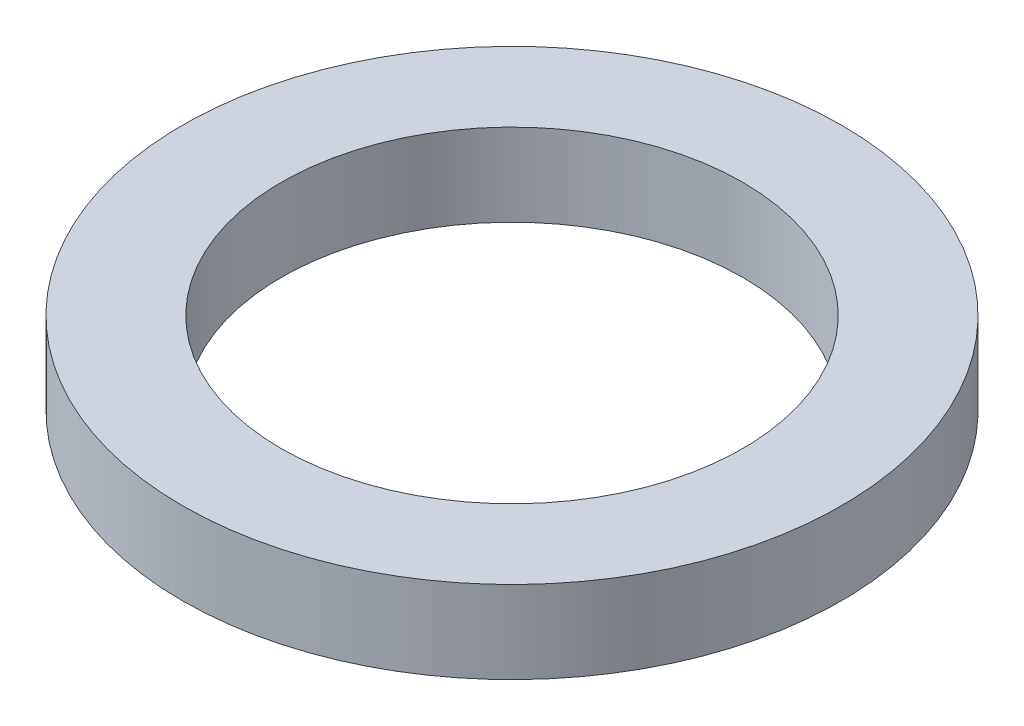
SolidWorks part; units mm, degrees
ref_plane "Front Plane" through (0, 0, 0) normal (0, 0, 1) x (1, 0, 0)
ref_plane "Top Plane" through (0, 0, 0) normal (0, 1, 0) x (1, 0, 0)
ref_plane "Right Plane" through (0, 0, 0) normal (1, 0, 0) x (0, 0, -1)
sketch "Sketch2" plane through (0, 0, 0) normal (0, 1, 0) x (1, 0, 0)
  circle A0 centre (0, 0) radius 12.7
  circle A1 centre (0, 0) radius 8.89
  dimension "D1" = 25.4
  dimension "D2" = 17.78
extrude "Boss-Extrude1" add sketch "Sketch2" along normal blind 3.175
